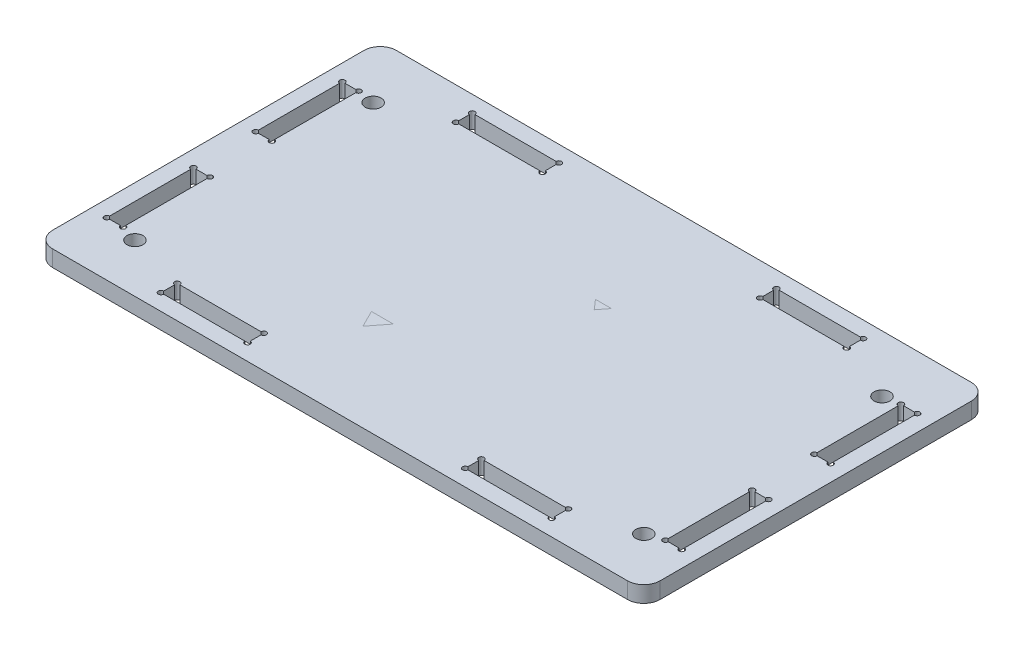
SolidWorks part; units mm, degrees
material "Acrylic (Medium-high impact)"
ref_plane "Front Plane" through (0, 0, 0) normal (0, 0, 1) x (1, 0, 0)
ref_plane "Top Plane" through (0, 0, 0) normal (0, 1, 0) x (1, 0, 0)
ref_plane "Right Plane" through (0, 0, 0) normal (1, 0, 0) x (0, 0, -1)
sketch "Sketch5" plane through (0, 0, 0) normal (0, 1, 0) x (1, 0, 0)
  line L0 (20, 50) -> (20, 0) construction
  line L1 (0, 0) -> (80, 0) construction
  line L2 (0, 0) -> (0, 50) construction
  line L3 (0, 50) -> (80, 50) construction
  line L4 (80, 50) -> (80, 0) construction
  line L5 (-10, 50) -> (0, 50) construction
  line L6 (-10, 0) -> (0, 0) construction
  line L7 (-10, 0) -> (-10, 50) construction
  line L8 (80, 50) -> (90, 50) construction
  line L9 (90, 0) -> (90, 50) construction
  line L10 (-13.2, -6) -> (93, -6)
  line L11 (-16.2, -3) -> (-16.2, 54.5)
  line L12 (-13.2, 57.5) -> (93, 57.5)
  line L13 (40, 50) -> (40, 0) construction
  line L14 (60, 50) -> (60, 0) construction
  line L15 (0, 25) -> (80, 25) construction
  line L16 (96, -3) -> (96, 54.5)
  line L17 (80, 0) -> (90, 0) construction
  circle A0 centre (-7, 3) radius 1.4732
  circle A1 centre (-7, 47) radius 1.4732
  circle A2 centre (87, 47) radius 1.4732
  circle A3 centre (87, 3) radius 1.4732
  arc A4 (-13.2, 57.5) -> (-16.2, 54.5) centre (-13.2, 54.5) ccw
  arc A5 (-16.2, -3) -> (-13.2, -6) centre (-13.2, -3) ccw
  arc A6 (93, -6) -> (96, -3) centre (93, -3) ccw
  arc A7 (96, 54.5) -> (93, 57.5) centre (93, 54.5) ccw
  line B0 (4.3, 54.5) -> (19.3, 54.5)
  line B1 (3.8, 54) -> (3.8, 52)
  line B2 (4.3, 51.5) -> (19.3, 51.5)
  line B3 (19.8, 54) -> (19.8, 52)
  arc B4 (4.3, 54.5) -> (3.8, 54) centre (3.8, 54.5) ccw
  arc B5 (3.8, 52) -> (4.3, 51.5) centre (3.8, 51.5) ccw
  arc B6 (19.3, 51.5) -> (19.8, 52) centre (19.8, 51.5) ccw
  arc B7 (19.8, 54) -> (19.3, 54.5) centre (19.8, 54.5) ccw
  line B8 (60.5, 54.5) -> (75.5, 54.5)
  line B9 (60, 54) -> (60, 52)
  line B10 (60.5, 51.5) -> (75.5, 51.5)
  line B11 (76, 54) -> (76, 52)
  arc B12 (60.5, 54.5) -> (60, 54) centre (60, 54.5) ccw
  arc B13 (60, 52) -> (60.5, 51.5) centre (60, 51.5) ccw
  arc B14 (75.5, 51.5) -> (76, 52) centre (76, 51.5) ccw
  arc B15 (76, 54) -> (75.5, 54.5) centre (76, 54.5) ccw
  line B16 (4.3, 0) -> (19.3, 0)
  line B17 (3.8, -0.5) -> (3.8, -2.5)
  line B18 (4.3, -3) -> (19.3, -3)
  line B19 (19.8, -0.5) -> (19.8, -2.5)
  arc B20 (4.3, 0) -> (3.8, -0.5) centre (3.8, 0) ccw
  arc B21 (3.8, -2.5) -> (4.3, -3) centre (3.8, -3) ccw
  arc B22 (19.3, -3) -> (19.8, -2.5) centre (19.8, -3) ccw
  arc B23 (19.8, -0.5) -> (19.3, 0) centre (19.8, 0) ccw
  line B24 (60.5, 0) -> (75.5, 0)
  line B25 (60, -0.5) -> (60, -2.5)
  line B26 (60.5, -3) -> (75.5, -3)
  line B27 (76, -0.5) -> (76, -2.5)
  arc B28 (60.5, 0) -> (60, -0.5) centre (60, 0) ccw
  arc B29 (60, -2.5) -> (60.5, -3) centre (60, -3) ccw
  arc B30 (75.5, -3) -> (76, -2.5) centre (76, -3) ccw
  arc B31 (76, -0.5) -> (75.5, 0) centre (76, 0) ccw
  line B32 (-13.2, 32) -> (-13.2, 47)
  line B33 (-12.7, 31.5) -> (-10.7, 31.5)
  line B34 (-10.2, 32) -> (-10.2, 47)
  line B35 (-12.7, 47.5) -> (-10.7, 47.5)
  arc B36 (-13.2, 32) -> (-12.7, 31.5) centre (-13.2, 31.5) ccw
  arc B37 (-10.7, 31.5) -> (-10.2, 32) centre (-10.2, 31.5) ccw
  arc B38 (-10.2, 47) -> (-10.7, 47.5) centre (-10.2, 47.5) ccw
  arc B39 (-12.7, 47.5) -> (-13.2, 47) centre (-13.2, 47.5) ccw
  line B40 (-13.2, 4.5) -> (-13.2, 19.5)
  line B41 (-12.7, 4) -> (-10.7, 4)
  line B42 (-10.2, 4.5) -> (-10.2, 19.5)
  line B43 (-12.7, 20) -> (-10.7, 20)
  arc B44 (-13.2, 4.5) -> (-12.7, 4) centre (-13.2, 4) ccw
  arc B45 (-10.7, 4) -> (-10.2, 4.5) centre (-10.2, 4) ccw
  arc B46 (-10.2, 19.5) -> (-10.7, 20) centre (-10.2, 20) ccw
  arc B47 (-12.7, 20) -> (-13.2, 19.5) centre (-13.2, 20) ccw
  line B48 (90, 32) -> (90, 47)
  line B49 (90.5, 31.5) -> (92.5, 31.5)
  line B50 (93, 32) -> (93, 47)
  line B51 (90.5, 47.5) -> (92.5, 47.5)
  arc B52 (90, 32) -> (90.5, 31.5) centre (90, 31.5) ccw
  arc B53 (92.5, 31.5) -> (93, 32) centre (93, 31.5) ccw
  arc B54 (93, 47) -> (92.5, 47.5) centre (93, 47.5) ccw
  arc B55 (90.5, 47.5) -> (90, 47) centre (90, 47.5) ccw
  line B56 (90, 4.5) -> (90, 19.5)
  line B57 (90.5, 4) -> (92.5, 4)
  line B58 (93, 4.5) -> (93, 19.5)
  line B59 (90.5, 20) -> (92.5, 20)
  arc B60 (90, 4.5) -> (90.5, 4) centre (90, 4) ccw
  arc B61 (92.5, 4) -> (93, 4.5) centre (93, 4) ccw
  arc B62 (93, 19.5) -> (92.5, 20) centre (93, 20) ccw
  arc B63 (90.5, 20) -> (90, 19.5) centre (90, 20) ccw
  dimension "D3" = 20
  dimension "D4" = 20
  dimension "D2" = 80
  dimension "D43" = 3
  dimension "D15" = 2.9464
  dimension "D12" = 3
  dimension "D18" = 2.9464
  dimension "D21" = 2.9464
  dimension "D27" = 3
  dimension "D29" = 3
  dimension "D38" = 3
  dimension "D40" = 3
  dimension "D39" = 20
  dimension "D46" = 3
  dimension "D49" = 10
  dimension "D7" = 10
  dimension "D13" = 6
  dimension "D23" = 3
  dimension "D20" = 3
  dimension "D19" = 3
  dimension "D33" = 3
  dimension "D37" = 20
  dimension "D34" = 3
  dimension "D35" = 3
  dimension "D36" = 3
  dimension "D24" = 2.9464
  dimension "D30" = 3
  dimension "D41" = 3
  dimension "D42" = 20
  dimension "D5" = 20
  dimension "D6" = 10
  dimension "D8" = 50
  dimension "D9" = 7.5
  dimension "D10" = 6.2
  dimension "D11" = 6
  dimension "D14" = 3
  dimension "D16" = 3
  dimension "D17" = 3
  dimension "D22" = 3
  dimension "D25" = 3
  dimension "D26" = 3
  dimension "D28" = 3
  dimension "D31" = 3
  dimension "D32" = 3
  dimension "D44" = 20
  dimension "D45" = 10
  dimension "D47" = 3
  dimension "D48" = 10
  dimension "D50" = 10
  dimension "D51" = 3
  dimension "D52" = 3
  dimension "D53" = 106.2
  dimension "D54" = 57.5
sketch_block_instance "Block3-1"
sketch_block "Block3" parameters "D3"=0.5, "D4"=0.5, "D5"=0.5, "D6"=0.5, "D1"=16, "D2"=3.2, "D7"=3.2, "D8"=3, "D9"=0.5, "D10"=0.5, "D11"=0.5, "D12"=0.5, "D13"=0.5, "D14"=0.5
sketch_block_instance "Block3-2"
sketch_block_instance "Block3-3"
sketch_block_instance "Block3-4"
sketch_block_instance "Block3-6"
sketch_block_instance "Block3-7"
sketch_block_instance "Block3-8"
sketch_block_instance "Block3-9"
extrude "Boss-Extrude1" add sketch "Sketch5" along normal blind 3
sketch "Sketch6" plane through (0, 3, 0) normal (0, 1, 0) x (1, 0, 0)
  line L0 (6.25, 4.0625) -> (10, 11.5625)
  line L1 (40, 50) -> (40, 0) construction
  line L2 (6.25, 20.9375) -> (13.75, 20.9375)
  line L3 (6.25, 20.9375) -> (6.25, 19.0625)
  line L4 (6.25, 4.0625) -> (13.75, 4.0625)
  line L5 (13.75, 20.9375) -> (13.75, 19.0625)
  line L6 (10, 11.5625) -> (13.75, 4.0625)
  line L7 (6.25, 19.0625) -> (13.75, 19.0625)
  line L8 (13.75, 17.1875) -> (6.25, 17.1875)
  line L9 (6.25, 15.3125) -> (13.75, 15.3125)
  line L10 (0, 0) -> (0, 50) construction
  line L11 (0, 50) -> (80, 50) construction
  line L12 (0, 25) -> (80, 25) construction
  line L13 (6.25, 17.1875) -> (6.25, 15.3125)
  line L14 (13.75, 17.1875) -> (13.75, 15.3125)
  line L15 (20, 50) -> (20, 0) construction
  line L16 (0, 0) -> (80, 0) construction
  line L17 (26.25, 29.0625) -> (30, 36.5625)
  line L18 (26.25, 45.9375) -> (33.75, 45.9375)
  line L19 (26.25, 45.9375) -> (26.25, 44.0625)
  line L20 (26.25, 29.0625) -> (33.75, 29.0625)
  line L21 (33.75, 45.9375) -> (33.75, 44.0625)
  line L22 (30, 36.5625) -> (33.75, 29.0625)
  line L23 (26.25, 44.0625) -> (33.75, 44.0625)
  line L24 (26.25, 36.5625) -> (33.75, 36.5625)
  line L25 (33.75, 36.5625) -> (30, 44.0625)
  line L26 (30, 44.0625) -> (26.25, 36.5625)
  line L27 (33.75, 20.9375) -> (30, 13.4375)
  line L28 (33.75, 4.0625) -> (26.25, 4.0625)
  line L29 (33.75, 4.0625) -> (33.75, 5.9375)
  line L30 (33.75, 20.9375) -> (26.25, 20.9375)
  line L31 (26.25, 4.0625) -> (26.25, 5.9375)
  line L32 (30, 13.4375) -> (26.25, 20.9375)
  line L33 (33.75, 5.9375) -> (26.25, 5.9375)
  line L34 (33.75, 13.4375) -> (26.25, 13.4375)
  line L35 (26.25, 13.4375) -> (30, 5.9375)
  line L36 (30, 5.9375) -> (33.75, 13.4375)
  line L37 (48, 32.64) -> (45, 36.0627)
  line L38 (6.25, 33.75) -> (13.75, 33.75)
  line L39 (6.25, 33.75) -> (6.25, 41.25)
  line L40 (6.25, 41.25) -> (13.75, 41.25)
  line L41 (13.75, 33.75) -> (13.75, 41.25)
  line L43 (48, 10.5) -> (45, 13.9227)
  line L44 (48, 8.5) -> (52, 8.5)
  line L45 (48, 8.5) -> (48, 10.5)
  line L46 (48, 30.64) -> (52, 30.64)
  line L47 (48, 30.64) -> (48, 32.64)
  line L48 (52, 8.5) -> (52, 10.5)
  line L49 (52, 30.64) -> (52, 32.64)
  line L50 (45, 36.0627) -> (55, 36.0627)
  line L51 (55, 36.0627) -> (52, 32.64)
  line L52 (45, 13.9227) -> (55, 13.9227)
  line L53 (55, 13.9227) -> (52, 10.5)
  line L54 (50.0038, 16.3533) -> (52.35, 16.3533)
  line L55 (60, 50) -> (60, 0) construction
  line L56 (70, 9) -> (70, 7.5)
  line L57 (67.2404, 16.6695) -> (66.8264, 17.2949)
  line L58 (70, 17.5) -> (70, 16)
  line L60 (71.9318, 9.5814) -> (71.5178, 10.2068)
  line L61 (68.0682, 15.4186) -> (68.4822, 14.7932)
  line L62 (72.7596, 8.3305) -> (73.1736, 7.7051)
  line L65 (71.5178, 10.2068) -> (71.0949, 8.1281)
  line L66 (71.0949, 8.1281) -> (73.1736, 7.7051)
  line L68 (66.8264, 17.2949) -> (68.9051, 16.8719)
  line L69 (68.9051, 16.8719) -> (68.4822, 14.7932)
  arc A0 (47.65, 37.4971) -> (48.35, 36.7829) centre (48, 37.14) ccw
  arc A1 (51.65, 36.7654) -> (52.35, 37.4795) centre (52, 37.1225) ccw
  arc A2 (47.65, 37.4971) -> (52.35, 37.4795) centre (49.9916, 35.2433) cw
  arc A3 (48.35, 36.7829) -> (51.65, 36.7654) centre (49.9919, 35.2445) cw
  arc A4 (46.65, 39.9971) -> (47.35, 39.2829) centre (47, 39.64) ccw
  arc A5 (52.65, 39.2654) -> (53.35, 39.9795) centre (53, 39.6225) ccw
  arc A6 (46.65, 39.9971) -> (53.35, 39.9795) centre (49.9912, 36.6208) cw
  arc A7 (47.35, 39.2829) -> (52.65, 39.2654) centre (49.9912, 36.6209) cw
  arc A8 (45.65, 42.4971) -> (46.35, 41.7829) centre (46, 42.14) ccw
  arc A9 (53.65, 41.7654) -> (54.35, 42.4795) centre (54, 42.1225) ccw
  arc A10 (46.35, 41.7829) -> (53.65, 41.7654) centre (49.9918, 38.3569) cw
  arc A11 (45.65, 42.4971) -> (54.35, 42.4795) centre (49.9917, 38.3558) cw
  arc A12 (47.65, 15.3571) -> (48.35, 14.6429) centre (48, 15) ccw
  arc A13 (51.65, 14.6254) -> (52.35, 15.3395) centre (52, 14.9825) ccw
  arc A14 (47.65, 15.3571) -> (52.35, 15.3395) centre (49.9916, 13.1033) cw
  arc A15 (48.35, 14.6429) -> (51.65, 14.6254) centre (49.9919, 13.1045) cw
  circle A16 centre (70, 37.5) radius 3.5
  circle A17 centre (70, 37.5) radius 2
  circle A18 centre (70, 37.5) radius 5
  arc A19 (68.0682, 15.4186) -> (70, 9) centre (70, 12.5) ccw
  arc A20 (71.9318, 9.5814) -> (70, 16) centre (70, 12.5) ccw
  arc A21 (67.2404, 16.6695) -> (70, 7.5) centre (70, 12.5) ccw
  arc A22 (72.7596, 8.3305) -> (70, 17.5) centre (70, 12.5) ccw
  dimension "D46" = 0.35
  dimension "D50" = 1
  dimension "D51" = 1
  dimension "D55" = 2.25
  dimension "D56" = 3.25
  dimension "D44" = 1
  dimension "D57" = 1
  dimension "D58" = 1
  dimension "D59" = 0.35
  dimension "D64" = 4.75
  dimension "D65" = 3.75
  dimension "D70" = 2.5
  dimension "D71" = 2.5
  dimension "D73" = 2
  dimension "D74" = 0.35
  dimension "D66" = 1
  dimension "D67" = 1
  dimension "D78" = 6
  dimension "D79" = 5
  dimension "D88" = 1
  dimension "D89" = 1
  dimension "D92" = 2.25
  dimension "D93" = 3.25
  dimension "D100" = 4
  dimension "D101" = 7
  dimension "D102" = 10
  dimension "D103" = 12.5
  dimension "D98" = 10
  dimension "D99" = 7
  dimension "D104" = 10
  dimension "D1" = 6.25
  dimension "D2" = 7.5
  dimension "D3" = 7.5
  dimension "D4" = 1.875
  dimension "D5" = 1.875
  dimension "D6" = 1.875
  dimension "D7" = 6.25
  dimension "D8" = 4.0625
  dimension "D9" = 6.25
  dimension "D10" = 4.0625
  dimension "D11" = 10
  dimension "D12" = 7.5
  dimension "D13" = 7.5
  dimension "D14" = 1.875
  dimension "D15" = 0
  dimension "D16" = 7.5
  dimension "D17" = 7.5
  dimension "D18" = 0
  dimension "D19" = 0
  dimension "D20" = 7.5
  dimension "D21" = 4.0625
  dimension "D22" = 6.25
  dimension "D23" = 7.5
  dimension "D24" = 7.5
  dimension "D25" = 1.875
  dimension "D26" = 3.75
  dimension "D27" = 7.5
  dimension "D28" = 7.5
  dimension "D29" = 7.5
  dimension "D30" = 0
  dimension "D31" = 0
  dimension "D32" = 6.25
  dimension "D33" = 4.0625
  dimension "D34" = 8.5
  dimension "D35" = 5
  dimension "D36" = 7.5
  dimension "D37" = 7.5
  dimension "D38" = 6.25
  dimension "D39" = 8.75
  dimension "D40" = 5.64
  dimension "D41" = 3
  dimension "D42" = 4
  dimension "D43" = 2
  dimension "D45" = 3
  dimension "D47" = 0.35
  dimension "D48" = 0.35
  dimension "D49" = 0.35
  dimension "D52" = 4.5
  dimension "D53" = 4
  dimension "D54" = 1
  dimension "D60" = 8
  dimension "D61" = 0.35
  dimension "D62" = 0.35
  dimension "D63" = 0.35
  dimension "D68" = 2.5
  dimension "D69" = 2.5
  dimension "D72" = 6
  dimension "D75" = 0.35
  dimension "D76" = 0.35
  dimension "D77" = 0.35
  dimension "D80" = 5
  dimension "D81" = 3
  dimension "D82" = 4
  dimension "D83" = 2
  dimension "D84" = 0.35
  dimension "D85" = 0.35
  dimension "D86" = 0.35
  dimension "D87" = 0.35
  dimension "D90" = 4.5
  dimension "D91" = 4
  dimension "D96" = 10
  dimension "D97" = 12.5
  dimension "D105" = 0.75
  dimension "D106" = 0.75
  dimension "D107" = 0.75
  dimension "D108" = 0.75
  dimension "D114" = 3
  dimension "D115" = 3
  dimension "D120" = 2
  dimension "D121" = 3
extrude "Boss-Extrude2" add sketch "Sketch6" against normal blind 0.2 separate body contours A18 A16 | A17 | L62 A22 L58 A20 L60 L65 L66 | L57 A21 L56 A19 L61 L69 L68 | L51 L50 L37 L47 L46 L49 | A0 A3 A1 A2 | A4 A7 A5 A6 | A11 A8 A10 A9 | L53 L52 L43 L45 L44 L48 | A12 A15 A13 A14 | L25 L26 L24 | L19 L23 L21 L18 | L22 L17 L20 | L32 L27 L30 | L35 L36 L34 | L29 L33 L31 L28 | L6 L0 L4 | L14 L8 L13 L9 | L3 L7 L5 L2 | L38 L41 L40 L39
